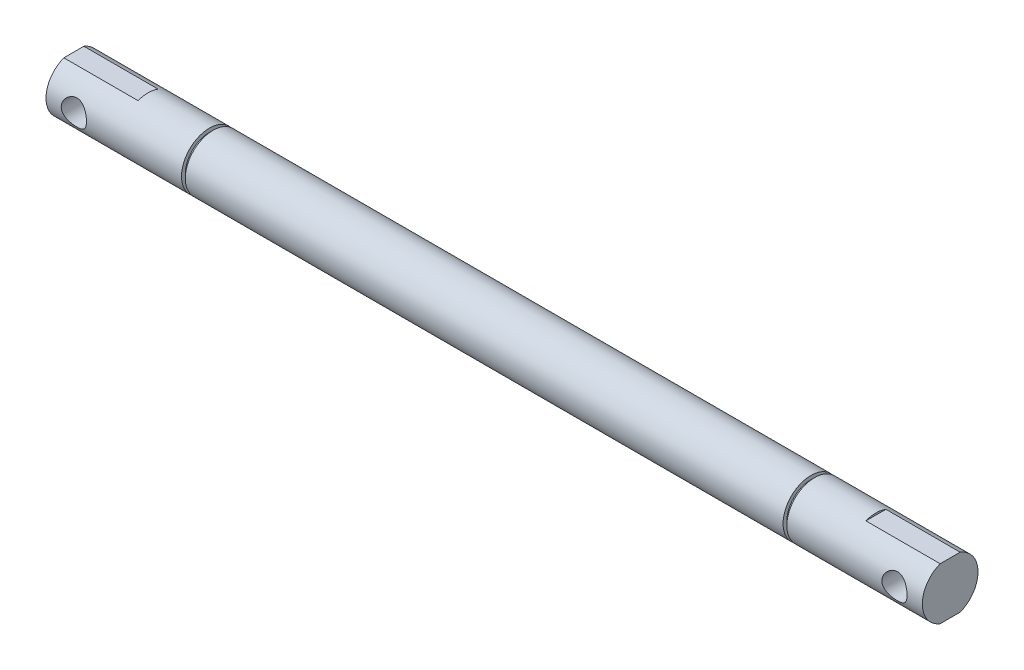
SolidWorks part; units mm, degrees
material "AISI 304"
ref_plane "Ön Düzlem" through (0, 0, 0) normal (0, 0, 1) x (1, 0, 0)
ref_plane "Üst Düzlem" through (0, 0, 0) normal (0, 1, 0) x (1, 0, 0)
ref_plane "Sağ Düzlem" through (0, 0, 0) normal (1, 0, 0) x (0, 0, -1)
sketch "Sketch1" plane through (0, 0, 0) normal (1, 0, 0) x (0, 0, -1)
  circle A0 centre (0, 0) radius 7.5
  dimension "D1" = 15
extrude "Boss-Extrude1" add sketch "Sketch1" along normal mid plane 236
sketch "Sketch2" plane through (0, 0, 0) normal (0, 0, 1) x (1, 0, 0)
  line L0 (118, 7.5) -> (-118, 7.5) construction
  line L1 (-81.5, 6.5) -> (-80.5, 6.5)
  line L2 (-81.5, 6.5) -> (-81.5, 8.5)
  line L3 (-81.5, 8.5) -> (-80.5, 8.5)
  line L4 (-80.5, 6.5) -> (-80.5, 8.5)
  line L5 (-81.5, 6.5) -> (-80.5, 8.5) construction
  line L6 (-81.5, 8.5) -> (-80.5, 6.5) construction
  line L7 (0, 0) -> (-20.2463, 0) construction
  point P0 (-81, 7.5)
  dimension "D1" = 81
  dimension "D2" = 1
  dimension "D3" = 1
revolve "Cut-Revolve1" cut sketch "Sketch2" angle 360 about L7
sketch "Sketch3" plane through (-118, 0, 0) normal (-1, 0, 0) x (0, 0, 1)
  line L0 (0, 0) -> (0, 7) construction
  line L1 (-6.2571, 7) -> (6.2571, 7)
  line L2 (6.2571, 7) -> (0.0537, 13.2034)
  line L3 (0.0537, 13.2034) -> (-6.2571, 7)
  point P6 (0, 7)
  dimension "D1" = 7
extrude "Cut-Extrude1" cut sketch "Sketch3" against normal blind 20
mirror "Mirror2" about plane through (0, 0, 0) normal (0, 1, 0) of "Cut-Extrude1"
ref_plane "Plane1" through (0, 0, 17.2214) normal (0, 0, 1) x (1, 0, 0)
hole_wizard "M8 Tapped Hole1" positions "Sketch4" profile "Sketch5" tap size "M8" standard "ISO" end condition through all
sketch "Sketch4" plane through (0, 0, 17.2214) normal (0, 0, 1) x (1, 0, 0)
  line L0 (-118, 7) -> (-118, -7) construction
  point P0 (-110.5, 0)
  dimension "D1" = 7.5
sketch "Sketch5" plane through (-110.5, 0, 17.2214) normal (1, 0, 0) x (0, -1, 0)
  line L0 (0, 0) -> (0, 24.7214)
  line L1 (0, 24.7214) -> (3.4, 24.7214)
  line L2 (3.4, 24.7214) -> (3.4, 0.625)
  line L3 (3.4, 0.625) -> (4.025, 0)
  line L5 (4.025, 0) -> (0, 0)
  line L6 (-3.4, 0.625) -> (-4.025, 0) construction
  line L11 (0, -6.35) -> (0, 107.95) construction
  dimension "Thru Tap Drill Dia." = 6.8
  dimension "Thru Tap Drill Depth" = 24.7214
  dimension "Near C'Sink Dia." = 8.05
  dimension "Near C'Sink Angle" = 90
cosmetic thread "Hole Thread1" parameters "D2"=8
mirror "Mirror4" about plane through (0, 0, 0) normal (1, 0, 0) of "M8 Tapped Hole1", "Mirror2", "Cut-Extrude1", "Cut-Revolve1"
cosmetic thread "Hole Thread3" parameters "D2"=8
